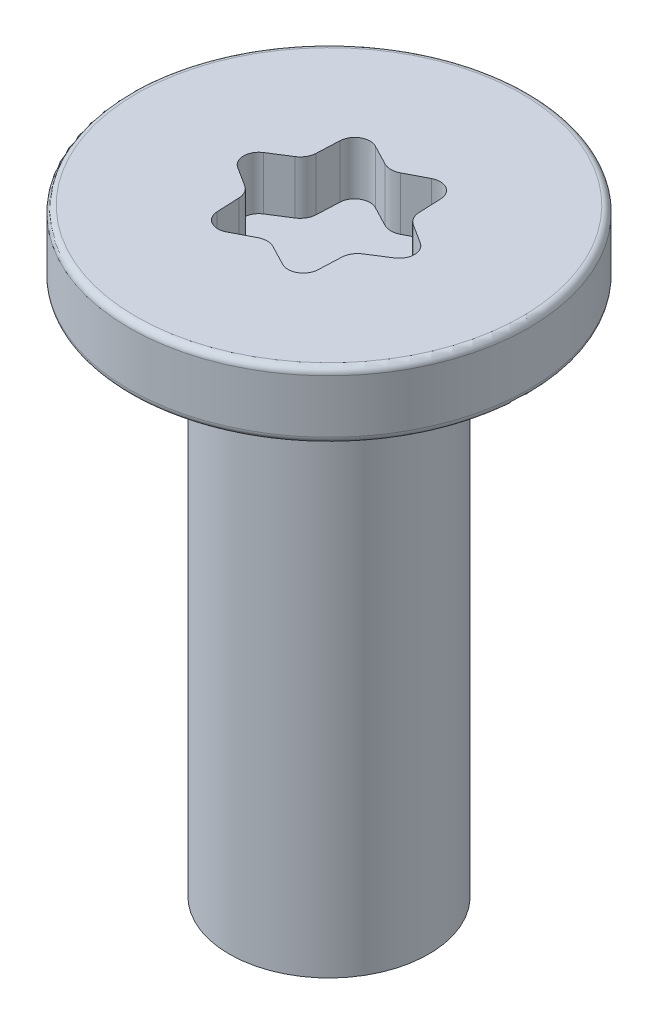
SolidWorks part; units mm, degrees
ref_plane "Front Plane" through (0, 0, 0) normal (0, 0, 1) x (1, 0, 0)
ref_plane "Top Plane" through (0, 0, 0) normal (0, 1, 0) x (1, 0, 0)
ref_plane "Right Plane" through (0, 0, 0) normal (1, 0, 0) x (0, 0, -1)
sketch "Sketch1" plane through (0, 0, 0) normal (1, 0, 0) x (0, 0, -1)
  line L0 (0, 0) -> (0, -9)
  line L1 (0, -9) -> (1.5, -9)
  line L2 (1.5, -9) -> (1.5, -1)
  line L3 (1.5, -1) -> (3, -1)
  line L4 (3, -1) -> (3, 0)
  line L5 (3, 0) -> (0, 0)
  line L6 (0, 0) -> (0, 12.752) construction
  dimension "D1" = 8
  dimension "D2" = 3
  dimension "D3" = 6
  dimension "D4" = 1
revolve "Revolve1" add sketch "Sketch1" angle 360 about L6
fillet "Fillet1" radius 0.1 2 edges at (0, -1, -3) (0, 0, -3)
sketch "Sketch2" plane through (0, 0, 0) normal (0, 1, 0) x (1, 0, 0)
  line L0 (-1.285, 0) -> (1.285, 0) construction
  line L1 (0, 0) -> (0, 1.285) construction
  line L2 (0, 0) -> (-0.6425, 1.1128) construction
  line L3 (-0.7573, 0.9236) -> (-0.7721, 0.5792)
  line L4 (-1.1785, 0.194) -> (-0.8877, 0.3791)
  line L5 (-0.4212, 1.1176) -> (-0.1156, 0.9583)
  line L6 (0.4212, 1.1176) -> (0.1156, 0.9583)
  line L7 (0.7573, 0.9236) -> (0.7721, 0.5792)
  line L8 (1.1785, 0.194) -> (0.8877, 0.3791)
  line L9 (1.1785, -0.194) -> (0.8877, -0.3791)
  line L10 (0.7573, -0.9236) -> (0.7721, -0.5792)
  line L11 (0.4212, -1.1176) -> (0.1156, -0.9583)
  line L12 (-0.4212, -1.1176) -> (-0.1156, -0.9583)
  line L13 (-0.7573, -0.9236) -> (-0.7721, -0.5792)
  line L14 (-1.1785, -0.194) -> (-0.8877, -0.3791)
  circle A0 centre (0, 0) radius 1.285
  circle A1 centre (0, 0) radius 0.93
  arc A2 (-0.6425, 1.1128) -> (-0.7573, 0.9236) centre (-0.5275, 0.9137) ccw
  arc A3 (-1.285, 0) -> (-1.1785, 0.194) centre (-1.055, 0) cw
  arc A4 (-0.8877, 0.3791) -> (-0.7721, 0.5792) centre (-1.0219, 0.59) ccw
  arc A5 (-0.6425, 1.1128) -> (-0.4212, 1.1176) centre (-0.5275, 0.9137) cw
  arc A6 (0.6425, 1.1128) -> (0.4212, 1.1176) centre (0.5275, 0.9137) ccw
  arc A7 (-0.1156, 0.9583) -> (0.1156, 0.9583) centre (0, 1.18) ccw
  arc A8 (0.6425, 1.1128) -> (0.7573, 0.9236) centre (0.5275, 0.9137) cw
  arc A9 (1.285, 0) -> (1.1785, 0.194) centre (1.055, 0) ccw
  arc A10 (0.7721, 0.5792) -> (0.8877, 0.3791) centre (1.0219, 0.59) ccw
  arc A11 (1.285, 0) -> (1.1785, -0.194) centre (1.055, 0) cw
  arc A12 (0.6425, -1.1128) -> (0.7573, -0.9236) centre (0.5275, -0.9137) ccw
  arc A13 (0.8877, -0.3791) -> (0.7721, -0.5792) centre (1.0219, -0.59) ccw
  arc A14 (0.6425, -1.1128) -> (0.4212, -1.1176) centre (0.5275, -0.9137) cw
  arc A15 (-0.6425, -1.1128) -> (-0.4212, -1.1176) centre (-0.5275, -0.9137) ccw
  arc A16 (0.1156, -0.9583) -> (-0.1156, -0.9583) centre (0, -1.18) ccw
  arc A17 (-0.6425, -1.1128) -> (-0.7573, -0.9236) centre (-0.5275, -0.9137) cw
  arc A18 (-1.285, 0) -> (-1.1785, -0.194) centre (-1.055, 0) ccw
  arc A19 (-0.7721, -0.5792) -> (-0.8877, -0.3791) centre (-1.0219, -0.59) ccw
  point P15 (0, 0)
  point P62 (0, 0)
  dimension "D1" = 2.57
  dimension "D2" = 1.86
  dimension "D4" = 0.23
  dimension "D5" = 0.25
  dimension "D3" = 60
  dimension "D6" = 6
extrude "Cut-Extrude1" cut sketch "Sketch2" against normal blind 0.8 contours A1 | A10 L7 A8 A6 L6 A7 A1 | A7 L5 A5 A2 L3 A4 A1 | A19 A1 A4 L4 A3 A18 L14 | A19 L13 A17 A15 L12 A16 A1 | A16 L11 A14 A12 L10 A13 A1 | A13 L9 A11 A9 L8 A10 A1
